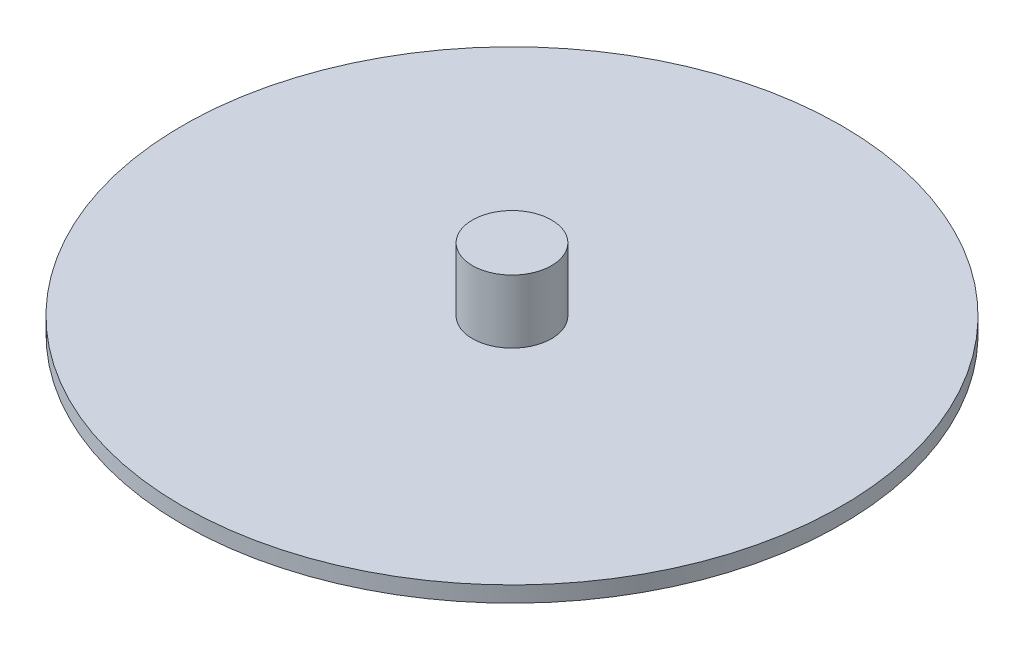
SolidWorks part; units mm, degrees
ref_plane "Front Plane" through (0, 0, 0) normal (0, 0, 1) x (1, 0, 0)
ref_plane "Top Plane" through (0, 0, 0) normal (0, 1, 0) x (1, 0, 0)
ref_plane "Right Plane" through (0, 0, 0) normal (1, 0, 0) x (0, 0, -1)
sketch "Sketch1" plane through (0, 0, 0) normal (0, 1, 0) x (1, 0, 0)
  circle A0 centre (0, 0) radius 125
  circle A1 centre (0, 0) radius 100 construction
  circle A2 centre (0, 100) radius 10
  circle A3 centre (100, 0) radius 10
  circle A4 centre (0, -100) radius 10
  circle A5 centre (-100, 0) radius 10
  point P15 (0, 0)
  dimension "D1" = 250
  dimension "D2" = 200
  dimension "D3" = 20
  dimension "D4" = 4
extrude "Boss-Extrude1" add sketch "Sketch1" along normal blind 3
sketch "Sketch2" plane through (0, 3, 0) normal (0, 1, 0) x (1, 0, 0)
  circle A0 centre (0, 0) radius 125
extrude "bắt chân drone" add sketch "Sketch2" along normal blind 3
sketch "Sketch3" plane through (0, 6, 0) normal (0, 1, 0) x (1, 0, 0)
  circle A0 centre (0, 0) radius 15
  dimension "D1" = 30
extrude "Trục gắn vào vòng bi (Thay đổi để match)" add sketch "Sketch3" along normal blind 24
